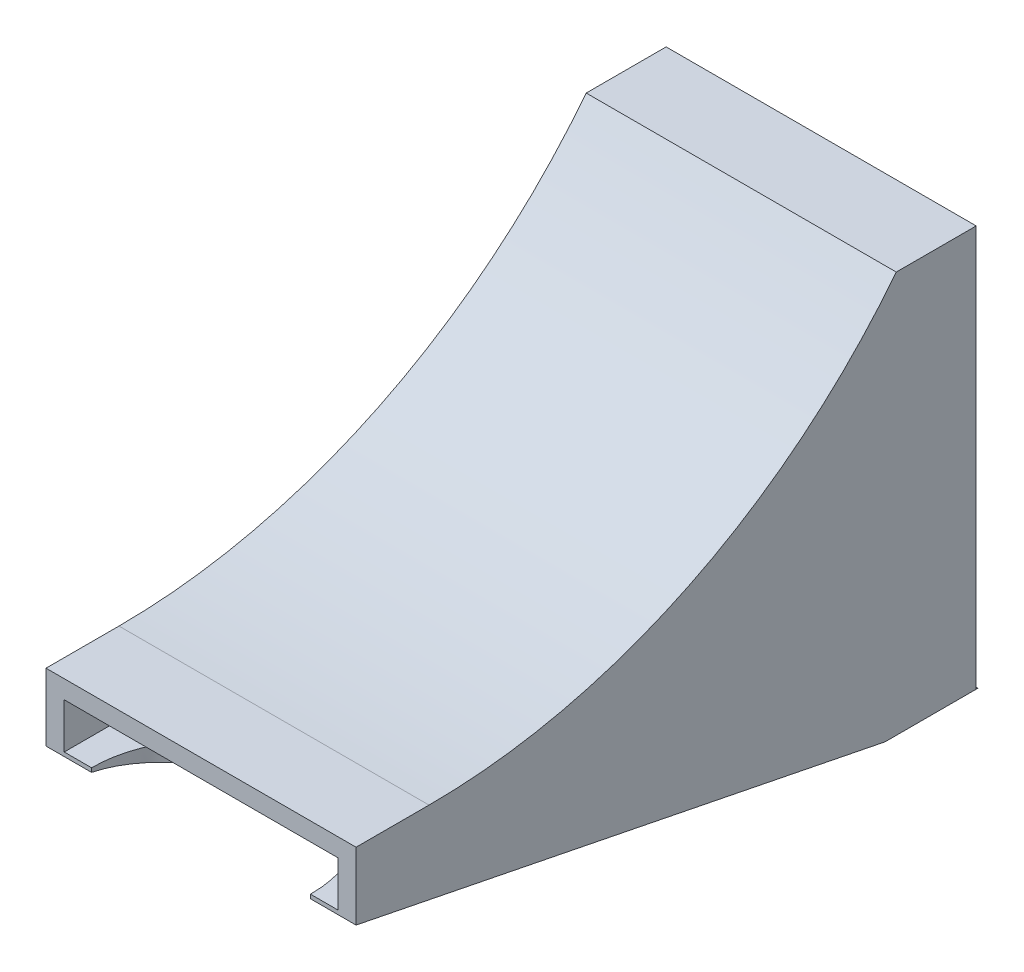
SolidWorks part; units mm, degrees
ref_plane "Front Plane" through (0, 0, 0) normal (0, 0, 1) x (1, 0, 0)
ref_plane "Top Plane" through (0, 0, 0) normal (0, 1, 0) x (1, 0, 0)
ref_plane "Right Plane" through (0, 0, 0) normal (1, 0, 0) x (0, 0, -1)
sketch "Sketch1" plane through (0, 0, 0) normal (0, 0, 1) x (1, 0, 0)
  line L1 (-7.5, 10) -> (7.5, 10)
  line L2 (-7.5, 10) -> (-7.5, -10)
  line L3 (-7.5, -10) -> (7.5, -10)
  line L4 (7.5, 10) -> (7.5, -10)
  line L5 (-7.5, 10) -> (7.5, -10) construction
  line L6 (-7.5, -10) -> (7.5, 10) construction
  line L7 (-8.5, -11) -> (8.5, -11)
  line L8 (-8.5, -11) -> (-8.5, 11)
  line L9 (-8.5, 11) -> (8.5, 11)
  line L10 (8.5, -11) -> (8.5, 11)
  line L11 (-8.5, -11) -> (8.5, 11) construction
  line L12 (-8.5, 11) -> (8.5, -11) construction
  point P0 (0, 0)
  point P6 (0, 0)
  dimension "D1" = 20
  dimension "D2" = 15
  dimension "D3" = 1
  dimension "D4" = 1
extrude "Boss-Extrude1" add sketch "Sketch1" along normal blind 30
sketch "Sketch2" plane through (8.5, 0, 0) normal (1, 0, 0) x (0, 0, -1)
  line L0 (0, -11) -> (0, 11) construction
  line L1 (-30, 11) -> (0, 11) construction
  circle A0 centre (-30, 31) radius 32.5
  dimension "D3" = 65
  dimension "D1" = 30
  dimension "D2" = 20
extrude "Cut-Extrude1" cut sketch "Sketch2" against normal through all
sketch "Sketch3" plane through (8.5, 0, 0) normal (1, 0, 0) x (0, 0, -1)
  line L0 (-30, -1.5) -> (-30, -2.5)
  line L1 (-4.3826, 11) -> (-3.1253, 11)
  line L2 (-4.3826, 11) -> (0, 11) construction
  arc A0 (-30, -2.5) -> (-3.1253, 11) centre (-30, 31) ccw
  arc A1 (-30, -1.5) -> (-4.3826, 11) centre (-30, 31) ccw construction
  arc A2 (-30, -1.5) -> (-4.3826, 11) centre (-30, 31) ccw
  dimension "D1" = 1
extrude "Boss-Extrude2" add sketch "Sketch3" against normal through all
sketch "Sketch4" plane through (-8.5, 0, 0) normal (-1, 0, 0) x (0, 0, 1)
  line L0 (5, -11) -> (30, -6)
  line L1 (30, -11) -> (0, -11) construction
  line L3 (30, -6) -> (30, -11)
  line L4 (30, -11) -> (5, -11)
  dimension "D1" = 5
  dimension "D2" = 25
extrude "Cut-Extrude2" cut sketch "Sketch4" against normal through all
sketch "Sketch5" plane through (-8.5, 0, 0) normal (-1, 0, 0) x (0, 0, 1)
  line L0 (5, -11) -> (30, -6)
  line L1 (30, -6) -> (30, -4.9802)
  line L2 (30, -1.5) -> (30, -6) construction
  line L3 (30, -4.9802) -> (-0.099, -11)
  line L4 (5, -11) -> (0, -11) construction
  line L5 (-0.099, -11) -> (5, -11)
  dimension "D1" = 1
extrude "Boss-Extrude3" add sketch "Sketch5" against normal through all
sketch "Sketch6" plane through (0, 0, 30) normal (0, 0, 1) x (1, 0, 0)
  line L0 (-8.5, -1.5) -> (8.5, -1.5)
  line L1 (8.5, -1.5) -> (8.5, -6)
  line L2 (8.5, -6) -> (-8.5, -6)
  line L3 (-8.5, -6) -> (-8.5, -1.5)
  line L4 (-7.5, -2.5) -> (-7.5, -4.9802)
  line L5 (-7.5, -4.9802) -> (7.5, -4.9802)
  line L6 (7.5, -4.9802) -> (7.5, -2.5)
  line L7 (7.5, -2.5) -> (-7.5, -2.5)
extrude "Boss-Extrude4" add sketch "Sketch6" along normal blind 4
sketch "Sketch7" plane through (-8.5, 0, 0) normal (-1, 0, 0) x (0, 0, 1)
  line L0 (24, -7.2) -> (34, -5.2)
  line L1 (30, -6) -> (5, -11) construction
  line L2 (34, -1.5) -> (34, -6) construction
  line L3 (34, -5.2) -> (34, -7.2)
  line L4 (34, -7.2) -> (24, -7.2)
  dimension "D1" = 2
extrude "Cut-Extrude3" cut sketch "Sketch7" against normal through all
sketch "Sketch8" plane through (0, -11.5385, 2.3077) normal (0, -0.9806, 0.1961) x (1, 0, 0)
  line L0 (8.5, 32.3199) -> (-8.5, 32.3199) construction
  circle A0 centre (0, 32.3199) radius 6
  dimension "D1" = 12
extrude "Cut-Extrude4" cut sketch "Sketch8" against normal up to next
